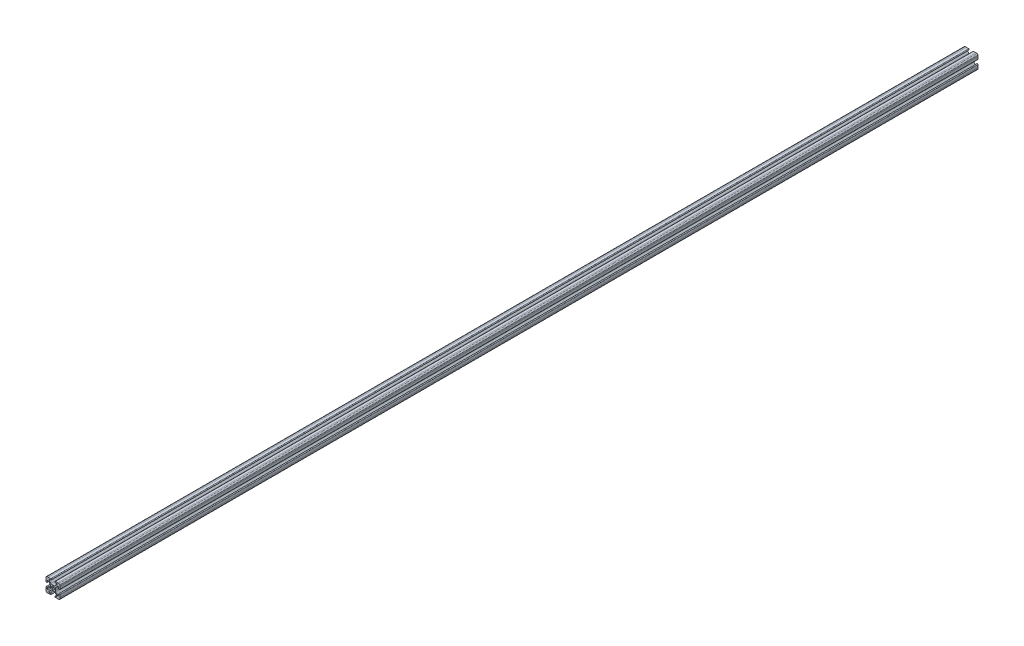
SolidWorks part; units mm, degrees
ref_plane "Front Plane" through (0, 0, 0) normal (0, 0, 1) x (1, 0, 0)
ref_plane "Top Plane" through (0, 0, 0) normal (0, 1, 0) x (1, 0, 0)
ref_plane "Right Plane" through (0, 0, 0) normal (1, 0, 0) x (0, 0, -1)
sketch "Model" plane through (0, 0, 0) normal (0, 0, 1) x (1, 0, 0)
  line L38 (50.6495, 75.4336) -> (50.2699, 75.4336)
  line L39 (50.2699, 75.4336) -> (50.2699, 75.8133)
  line L40 (50.66, 72.9999) -> (53.7746, 72.9999)
  line L41 (56.0196, 72.0699) -> (59.2642, 68.8254)
  line L42 (58.5103, 67.0916) -> (56.5725, 67.1592)
  line L43 (56.498, 65.0269) -> (60.6773, 64.881)
  line L44 (60.6773, 64.881) -> (62.7107, 64.881)
  line L45 (64.7173, 66.8876) -> (64.7173, 68.921)
  line L46 (64.7173, 68.921) -> (64.5713, 73.1002)
  line L47 (62.439, 73.0257) -> (62.5067, 71.0879)
  line L48 (60.7729, 70.334) -> (57.5283, 73.5786)
  line L49 (56.5984, 75.8237) -> (56.5984, 78.9383)
  line L50 (57.5283, 81.1833) -> (60.7729, 84.4279)
  line L51 (62.5067, 83.674) -> (62.439, 81.7362)
  line L52 (64.5713, 81.6617) -> (64.7173, 85.841)
  line L53 (64.7173, 85.841) -> (64.7173, 87.8744)
  line L54 (62.7107, 89.881) -> (60.6773, 89.881)
  line L55 (60.6773, 89.881) -> (56.498, 89.735)
  line L56 (56.5725, 87.6027) -> (58.5103, 87.6704)
  line L57 (59.2642, 85.9366) -> (56.0196, 82.692)
  line L58 (53.7746, 81.7621) -> (50.66, 81.7621)
  line L59 (48.4149, 82.692) -> (45.1703, 85.9366)
  line L60 (45.9242, 87.6704) -> (47.862, 87.6027)
  line L61 (47.9365, 89.735) -> (43.7573, 89.881)
  line L62 (43.7573, 89.881) -> (41.7239, 89.881)
  line L63 (39.7173, 87.8744) -> (39.7173, 85.841)
  line L64 (39.7173, 85.841) -> (39.8632, 81.6617)
  line L65 (41.9955, 81.7362) -> (41.9278, 83.674)
  line L66 (43.6616, 84.4279) -> (46.9062, 81.1833)
  line L67 (47.8361, 78.9383) -> (47.8361, 75.8237)
  line L68 (46.9062, 73.5786) -> (43.6616, 70.334)
  line L69 (41.9278, 71.0879) -> (41.9955, 73.0257)
  line L70 (39.8632, 73.1002) -> (39.7173, 68.921)
  line L71 (39.7173, 68.921) -> (39.7173, 66.8876)
  line L72 (41.7239, 64.881) -> (43.7573, 64.881)
  line L73 (43.7573, 64.881) -> (47.9365, 65.0269)
  line L74 (47.862, 67.1592) -> (45.9242, 67.0916)
  line L75 (45.1703, 68.8254) -> (48.4149, 72.0699)
  arc A29 (50.6495, 75.4336) -> (50.2699, 75.8133) centre (52.2173, 77.381) ccw
  arc A30 (56.0196, 72.0699) -> (53.7746, 72.9999) centre (53.7746, 69.8249) ccw
  arc A31 (58.5103, 67.0916) -> (59.2642, 68.8254) centre (58.5458, 68.1069) ccw
  arc A32 (56.5725, 67.1592) -> (56.498, 65.0269) centre (56.5353, 66.0931) ccw
  arc A33 (62.7107, 64.881) -> (64.7173, 66.8876) centre (62.7107, 66.8876) ccw
  arc A34 (64.5713, 73.1002) -> (62.439, 73.0257) centre (63.5052, 73.063) ccw
  arc A35 (60.7729, 70.334) -> (62.5067, 71.0879) centre (61.4913, 71.0525) ccw
  arc A36 (56.5984, 75.8237) -> (57.5283, 73.5786) centre (59.7734, 75.8237) ccw
  arc A37 (57.5283, 81.1833) -> (56.5984, 78.9383) centre (59.7734, 78.9383) ccw
  arc A38 (62.5067, 83.674) -> (60.7729, 84.4279) centre (61.4913, 83.7095) ccw
  arc A39 (62.439, 81.7362) -> (64.5713, 81.6617) centre (63.5052, 81.699) ccw
  arc A40 (64.7173, 87.8744) -> (62.7107, 89.881) centre (62.7107, 87.8744) ccw
  arc A41 (56.498, 89.735) -> (56.5725, 87.6027) centre (56.5353, 88.6689) ccw
  arc A42 (59.2642, 85.9366) -> (58.5103, 87.6704) centre (58.5458, 86.655) ccw
  arc A43 (53.7746, 81.7621) -> (56.0196, 82.692) centre (53.7746, 84.9371) ccw
  arc A44 (48.4149, 82.692) -> (50.66, 81.7621) centre (50.66, 84.9371) ccw
  arc A45 (45.9242, 87.6704) -> (45.1703, 85.9366) centre (45.8887, 86.655) ccw
  arc A46 (47.862, 87.6027) -> (47.9365, 89.735) centre (47.8993, 88.6689) ccw
  arc A47 (41.7239, 89.881) -> (39.7173, 87.8744) centre (41.7239, 87.8744) ccw
  arc A48 (39.8632, 81.6617) -> (41.9955, 81.7362) centre (40.9293, 81.699) ccw
  arc A49 (43.6616, 84.4279) -> (41.9278, 83.674) centre (42.9432, 83.7095) ccw
  arc A50 (47.8361, 78.9383) -> (46.9062, 81.1833) centre (44.6611, 78.9383) ccw
  arc A51 (46.9062, 73.5786) -> (47.8361, 75.8237) centre (44.6611, 75.8237) ccw
  arc A52 (41.9278, 71.0879) -> (43.6616, 70.334) centre (42.9432, 71.0525) ccw
  arc A53 (41.9955, 73.0257) -> (39.8632, 73.1002) centre (40.9293, 73.063) ccw
  arc A54 (39.7173, 66.8876) -> (41.7239, 64.881) centre (41.7239, 66.8876) ccw
  arc A55 (47.9365, 65.0269) -> (47.862, 67.1592) centre (47.8993, 66.0931) ccw
  arc A56 (45.1703, 68.8254) -> (45.9242, 67.0916) centre (45.8887, 68.1069) ccw
  arc A57 (50.66, 72.9999) -> (48.4149, 72.0699) centre (50.66, 69.8249) ccw
extrude "Boss-Extrude1" add sketch "Model" along normal blind 1650.492
